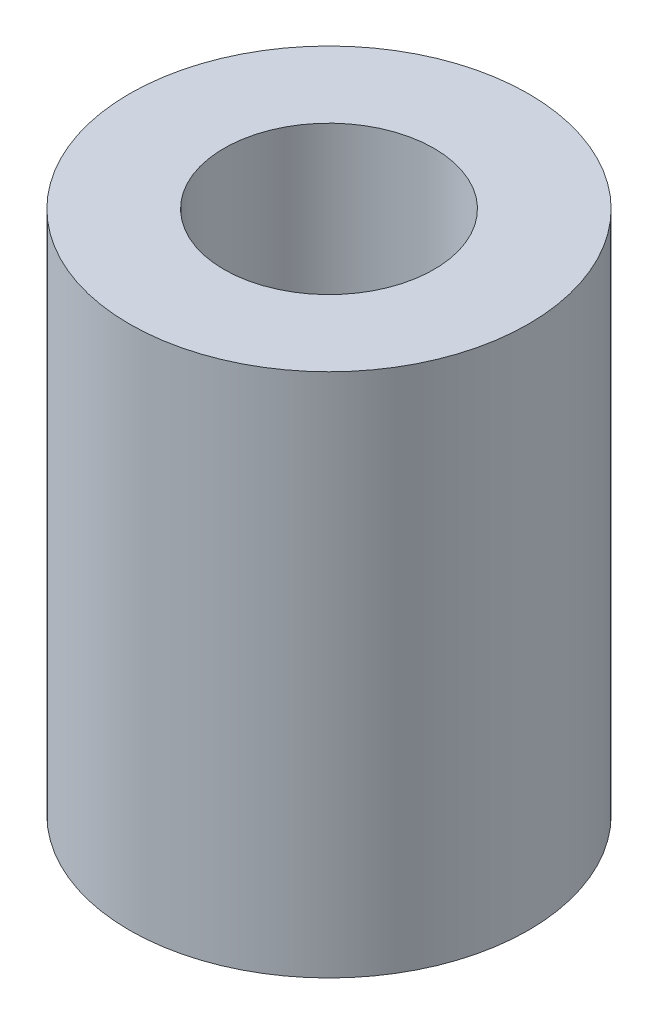
SolidWorks part; units mm, degrees
ref_plane "Front Plane" through (0, 0, 0) normal (0, 0, 1) x (1, 0, 0)
ref_plane "Top Plane" through (0, 0, 0) normal (0, 1, 0) x (1, 0, 0)
ref_plane "Right Plane" through (0, 0, 0) normal (1, 0, 0) x (0, 0, -1)
sketch "Sketch1" plane through (0, 0, 0) normal (0, 1, 0) x (1, 0, 0)
  circle A0 centre (0, 0) radius 9.5
  dimension "D1" = 19
extrude "Boss-Extrude1" add sketch "Sketch1" along normal blind 25
sketch "Sketch2" plane through (0, 25, 0) normal (0, 1, 0) x (1, 0, 0)
  circle A0 centre (0, 0) radius 5
  dimension "D1" = 10
extrude "Cut-Extrude1" cut sketch "Sketch2" against normal offset from surface (20 mm away) 5 up to face at (0, 0, 9.5)
sketch "Sketch3" plane through (0, 0, 0) normal (0, -1, 0) x (1, 0, 0)
  circle A0 centre (0, 0) radius 2
  dimension "D1" = 4
extrude "Cut-Extrude2" cut sketch "Sketch3" against normal through all
